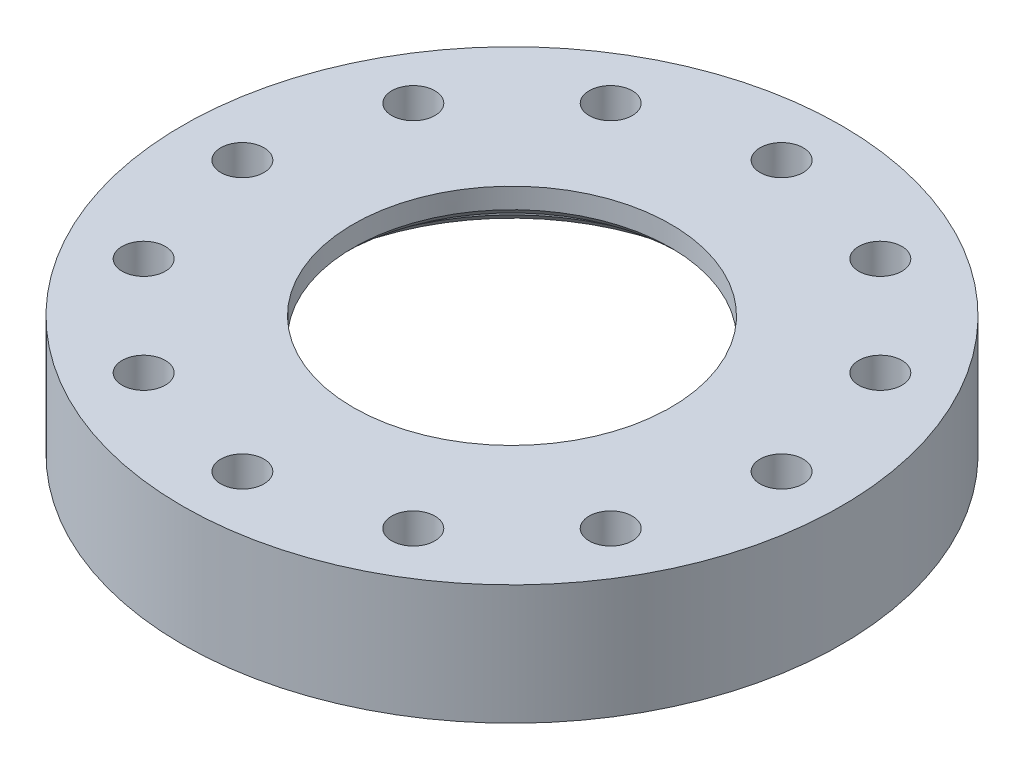
SolidWorks part; units mm, degrees
ref_plane "Front Plane" through (0, 0, 0) normal (0, 0, 1) x (1, 0, 0)
ref_plane "Top Plane" through (0, 0, 0) normal (0, 1, 0) x (1, 0, 0)
ref_plane "Right Plane" through (0, 0, 0) normal (1, 0, 0) x (0, 0, -1)
sketch "Sketch1" plane through (0, 0, 0) normal (0, 0, 1) x (1, 0, 0)
  line L0 (-25.75, 0) -> (-27.5, 0)
  line L1 (-27.5, 0) -> (-27.5, 10)
  line L2 (-27.5, 10) -> (-13.25, 10)
  line L4 (-16.25, 5) -> (-19.25, 5)
  line L6 (0, 0) -> (0, -6.1848) construction
  line L7 (-19.25, 5) -> (-19.25, 7)
  line L8 (-19.25, 7) -> (-25.75, 7)
  line L9 (-25.75, 7) -> (-25.75, 0)
  line L10 (-16.25, 5) -> (-16.25, 7.5)
  line L11 (-16.25, 7.5) -> (-13.25, 7.5)
  line L12 (-13.25, 7.5) -> (-13.25, 10)
  point P5 (-16.25, 7.6245)
  point P11 (0, 0)
  point P14 (0, 0)
  dimension "D1" = 3
  dimension "D2" = 51.5
  dimension "D3" = 7
  dimension "D4" = 6.5
  dimension "D5" = 55
  dimension "D6" = 32.5
  dimension "D7" = 2
  dimension "D8" = 0.5
  dimension "D9" = 3
revolve "Revolve1" add sketch "Sketch1" angle 360 about L6
hole_wizard "M3 Clearance Hole1" positions "Sketch2" profile "Sketch3" hole size "M3" standard "ISO" end condition through all
sketch "Sketch2" plane through (0, 10, 0) normal (0, 1, 0) x (1, 0, 0)
  circle A0 centre (0, 0) radius 22.5 construction
  point P0 (-22.5, 0)
  point P15 (-19.4856, 11.25)
  point P16 (-11.25, 19.4856)
  point P17 (0, 22.5)
  point P18 (11.25, 19.4856)
  point P19 (19.4856, 11.25)
  point P20 (22.5, 0)
  point P21 (19.4856, -11.25)
  point P22 (11.25, -19.4856)
  point P23 (0, -22.5)
  point P24 (-11.25, -19.4856)
  point P25 (-19.4856, -11.25)
  dimension "D1" = 45
  dimension "D2" = 12
sketch "Sketch3" plane through (-22.5, 10, 0) normal (1, 0, 0) x (0, 0, 1)
  line L0 (0, 0) -> (0, 10)
  line L1 (0, 10) -> (1.8, 10)
  line L2 (1.8, 10) -> (1.8, 0)
  line L5 (1.8, 0) -> (0, 0)
  line L11 (0, -6.35) -> (0, 107.95) construction
  dimension "Thru Hole Dia." = 3.6
  dimension "Thru Hole Depth" = 10
chamfer "Chamfer1" distance 0.8 angle 45 2 edges at (0, 7.5, 13.25) (0, 5, 16.25)
